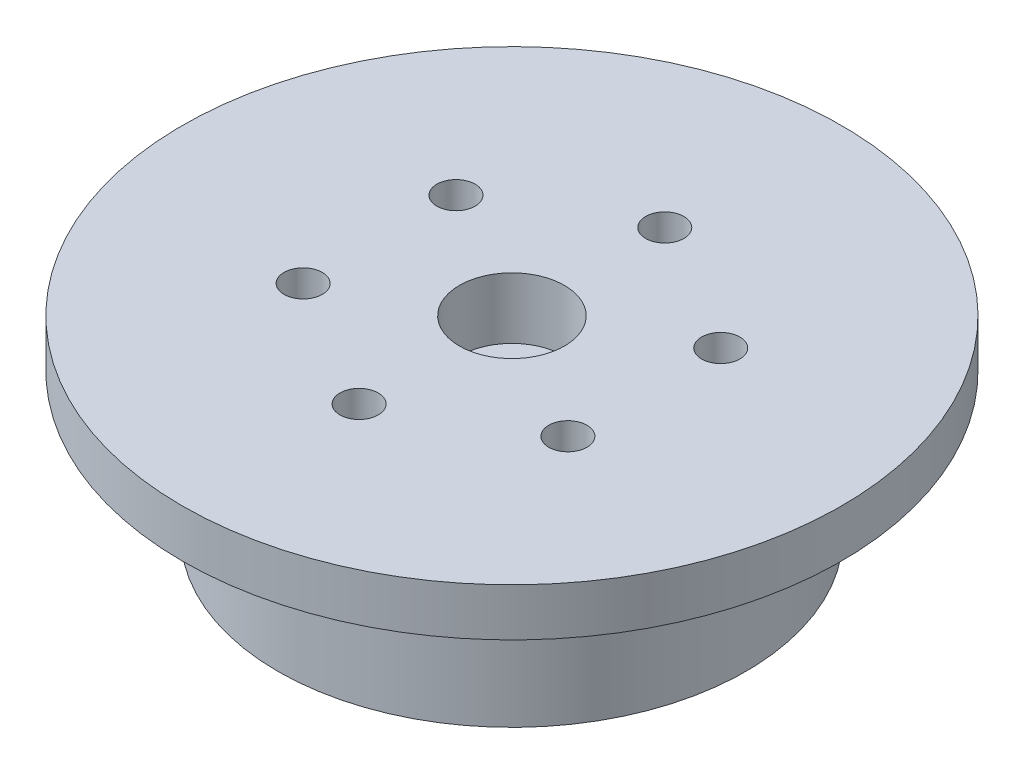
SolidWorks part; units mm, degrees
ref_plane "Alzado" through (0, 0, 0) normal (0, 0, 1) x (1, 0, 0)
ref_plane "Planta" through (0, 0, 0) normal (0, 1, 0) x (1, 0, 0)
ref_plane "Vista lateral" through (0, 0, 0) normal (1, 0, 0) x (0, 0, -1)
sketch "Croquis1" plane through (0, 0, 0) normal (0, 1, 0) x (1, 0, 0)
  circle A0 centre (0, 0) radius 34.5
  dimension "D1" = 69
extrude "Saliente-Extruir1" add sketch "Croquis1" along normal blind 5
sketch "Croquis2" plane through (0, 0, 0) normal (0, -1, 0) x (1, 0, 0)
  circle A0 centre (0, 0) radius 24.5
  dimension "D1" = 49
extrude "Saliente-Extruir2" add sketch "Croquis2" along normal blind 15
sketch "Croquis3" plane through (0, -15, 0) normal (0, -1, 0) x (1, 0, 0)
  circle A1 centre (0, 0) radius 6.85
  dimension "D1" = 13.7
extrude "Saliente-Extruir3" add sketch "Croquis3" along normal blind 30
sketch "Croquis4" plane through (0, 5, 0) normal (0, 1, 0) x (1, 0, 0)
  circle A0 centre (0, 0) radius 16 construction
  circle A1 centre (0, 16) radius 2
  dimension "D1" = 32
  dimension "D2" = 4
extrude "Cortar-Extruir1" cut sketch "Croquis4" against normal blind 10
pattern_circular "MatrizC1" count 6 over 360 about axis through (0, 0, 0) along (0, 1, 0) of "Cortar-Extruir1"
sketch "Croquis7" plane through (0, -45, 0) normal (0, -1, 0) x (1, 0, 0)
  line L1 (-6.3775, 2.5) -> (-3.4775, 2.5)
  line L2 (-6.3775, -2.5) -> (-3.4775, -2.5)
  line L3 (-3.4775, 2.5) -> (-3.4775, -2.5)
  circle A0 centre (0, 0) radius 6.85 construction
  circle A1 centre (0, 0) radius 6.85 construction
  arc A2 (-6.3775, 2.5) -> (-6.3775, -2.5) centre (0, 0) ccw
  point P6 (-3.4775, 0)
  dimension "D1" = 5
  dimension "D2" = 2.9
extrude "Cortar-Extruir2" cut sketch "Croquis7" against normal up to surface (30 mm away) up to face at (0, -15, -6.85)
sketch "Sketch1" plane through (0, -45, 0) normal (0, -1, 0) x (1, 0, 0)
  line L0 (-6.3775, -2.5) -> (-9.35, -2.5)
  line L1 (-9.35, -2.5) -> (-9.35, 2.5)
  line L2 (-9.35, 2.5) -> (-6.3775, 2.5)
  line L3 (-6.3775, 2.5) -> (-3.4775, 2.5)
  line L4 (-3.4775, 2.5) -> (-3.4775, -2.5)
  line L5 (-3.4775, -2.5) -> (-6.3775, -2.5)
  line L6 (-6.3775, 2.5) -> (-3.4775, 2.5) construction
  line L7 (-3.4775, 2.5) -> (-3.4775, -2.5) construction
  line L8 (-3.4775, -2.5) -> (-6.3775, -2.5) construction
  line L9 (0, 0) -> (-6.85, 0) construction
  arc A1 (-6.3775, -2.5) -> (-6.3775, 2.5) centre (0, 0) ccw
  arc A2 (-6.3775, -2.5) -> (-6.3775, 2.5) centre (0, 0) ccw
  point P10 (0, 0)
  point P11 (0, 0)
  point P12 (0, 0)
  point P13 (-3.4775, 0)
  point P14 (-0.247, 0)
  dimension "D2" = 2.5
  dimension "D1" = 0
extrude "Cut-Extrude1" cut sketch "Sketch1" against normal offset from surface (40 mm away) 10 up to face at (12.1244, 5, -7)
hole_wizard "CBORE for M6 Hex Socket Head Cap Screw1" positions "Sketch3" profile "Sketch5" counterbore size "M6" standard "ISO" end condition through all
sketch "Sketch3" plane through (0, 5, 0) normal (0, 1, 0) x (1, 0, 0)
  point P0 (0, 0)
sketch "Sketch5" plane through (0, 5, 0) normal (1, 0, 0) x (0, 0, 1)
  line L0 (0, 0) -> (0, 20)
  line L1 (0, 20) -> (3.3, 20)
  line L3 (3.3, 20) -> (3.3, 6.4)
  line L4 (3.3, 6.4) -> (5.5, 6.4)
  line L5 (5.5, 6.4) -> (5.5, 0)
  line L7 (5.5, 0) -> (0, 0)
  line L11 (0, -6.35) -> (0, 107.95) construction
  dimension "Thru Hole Dia." = 6.6
  dimension "Thru Hole Depth" = 20
  dimension "C'Bore Dia." = 11
  dimension "C'Bore Depth" = 6.4
